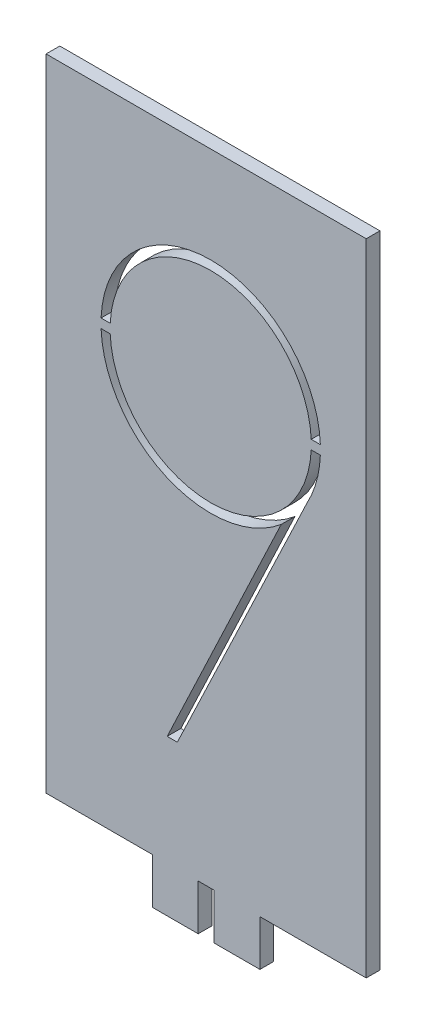
SolidWorks part; units mm, degrees
material "Glas"
ref_plane "Ebene vorne" through (0, 0, 0) normal (0, 0, 1) x (1, 0, 0)
ref_plane "Ebene oben" through (0, 0, 0) normal (0, 1, 0) x (1, 0, 0)
ref_plane "Ebene rechts" through (0, 0, 0) normal (1, 0, 0) x (0, 0, -1)
sketch "Skizze1" plane through (0, 0, 0) normal (0, 0, 1) x (1, 0, 0)
  line L1 (0, 0) -> (35, 0)
  line L2 (0, 0) -> (0, 75)
  line L3 (0, 75) -> (35, 75)
  line L4 (35, 0) -> (35, 75)
  dimension "D1" = 35
  dimension "D2" = 75
extrude "Aufsatz-Linear austragen1" add sketch "Skizze1" along normal blind 1.5
sketch "Skizze2" plane through (0, 0, 1.5) normal (0, 0, 1) x (1, 0, 0)
  line L0 (0, 0) -> (35, 0) construction
  line L1 (0, 0) -> (11.63, 0)
  line L2 (0, 0) -> (0, 5)
  line L3 (0, 5) -> (11.63, 5)
  line L4 (11.63, 0) -> (11.63, 5)
  line L5 (23.38, 5) -> (35, 5)
  line L6 (23.38, 5) -> (23.38, 0)
  line L7 (23.38, 0) -> (35, 0)
  line L8 (35, 5) -> (35, 0)
  line L9 (16.63, 0) -> (18.38, 0)
  line L10 (16.63, 0) -> (16.63, 5)
  line L11 (16.63, 5) -> (18.38, 5)
  line L12 (18.38, 0) -> (18.38, 5)
  dimension "D1" = 5
  dimension "D2" = 5
  dimension "D3" = 5
  dimension "D4" = 11.63
  dimension "D5" = 1.75
  dimension "D6" = 5
extrude "Schnitt-Linear austragen1" cut sketch "Skizze2" against normal blind 1.5
sketch "Skizze13" plane through (0, 0, 1.5) normal (0, 0, 1) x (1, 0, 0)
  line L0 (35, 75) -> (0, 75) construction
  line L1 (35, 5) -> (35, 75) construction
  circle A0 centre (18, 52.5) radius 11
  circle A1 centre (18, 52.5) radius 12
  point P3 (0, 0)
  dimension "D1" = 24
  dimension "D2" = 22
  dimension "D3" = 22.5
  dimension "D4" = 17
extrude "Schnitt-Linear austragen10" cut sketch "Skizze13" against normal blind 20
sketch "Skizze14" plane through (0, 0, 1.5) normal (0, 0, 1) x (1, 0, 0)
  line L0 (35, 75) -> (0, 75) construction
  line L1 (4.7872, 53) -> (31.9933, 53)
  line L2 (4.7872, 53) -> (4.7872, 52)
  line L3 (4.7872, 52) -> (31.9933, 52)
  line L4 (31.9933, 53) -> (31.9933, 52)
  dimension "D1" = 1
  dimension "D2" = 22
extrude "Aufsatz-Linear austragen2" add sketch "Skizze14" against normal blind 1.5
sketch "Skizze15" plane through (0, 0, 1.5) normal (0, 0, 1) x (1, 0, 0)
  line L1 (14.3478, 17) -> (13.2412, 17)
  line L2 (13.2412, 17) -> (27.2316, 46.5185)
  line L3 (27.2316, 46.5185) -> (29.4062, 48.7718)
  line L4 (11.63, 5) -> (0, 5) construction
  line L5 (14.3478, 17) -> (28.5323, 46.7494)
  line L6 (28.5323, 46.7494) -> (29.2835, 48.4157)
  line L7 (29.2835, 48.4157) -> (29.4062, 48.7718)
  arc A0 (6.0104, 52) -> (29.9896, 52) centre (18, 52.5) ccw construction
  arc A1 (7.0114, 52) -> (28.9886, 52) centre (18, 52.5) ccw construction
  dimension "D3" = 3.2282
  dimension "D2" = 12
extrude "Schnitt-Linear austragen11" cut sketch "Skizze15" against normal blind 20
